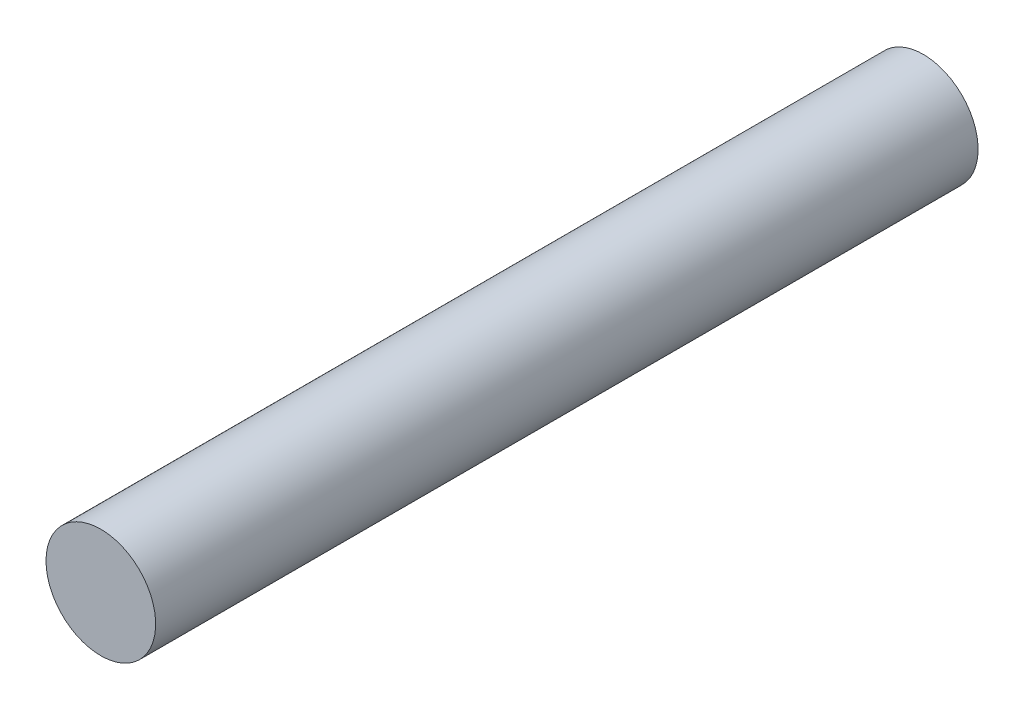
SolidWorks part; units mm, degrees
ref_plane "前视基准面" through (0, 0, 0) normal (0, 0, 1) x (1, 0, 0)
ref_plane "上视基准面" through (0, 0, 0) normal (0, 1, 0) x (1, 0, 0)
ref_plane "右视基准面" through (0, 0, 0) normal (1, 0, 0) x (0, 0, -1)
sketch "草图1" plane through (0, 0, 0) normal (0, 0, 1) x (1, 0, 0)
  circle A0 centre (0, 0) radius 3
extrude "凸台-拉伸1" add sketch "草图1" along normal blind 45
